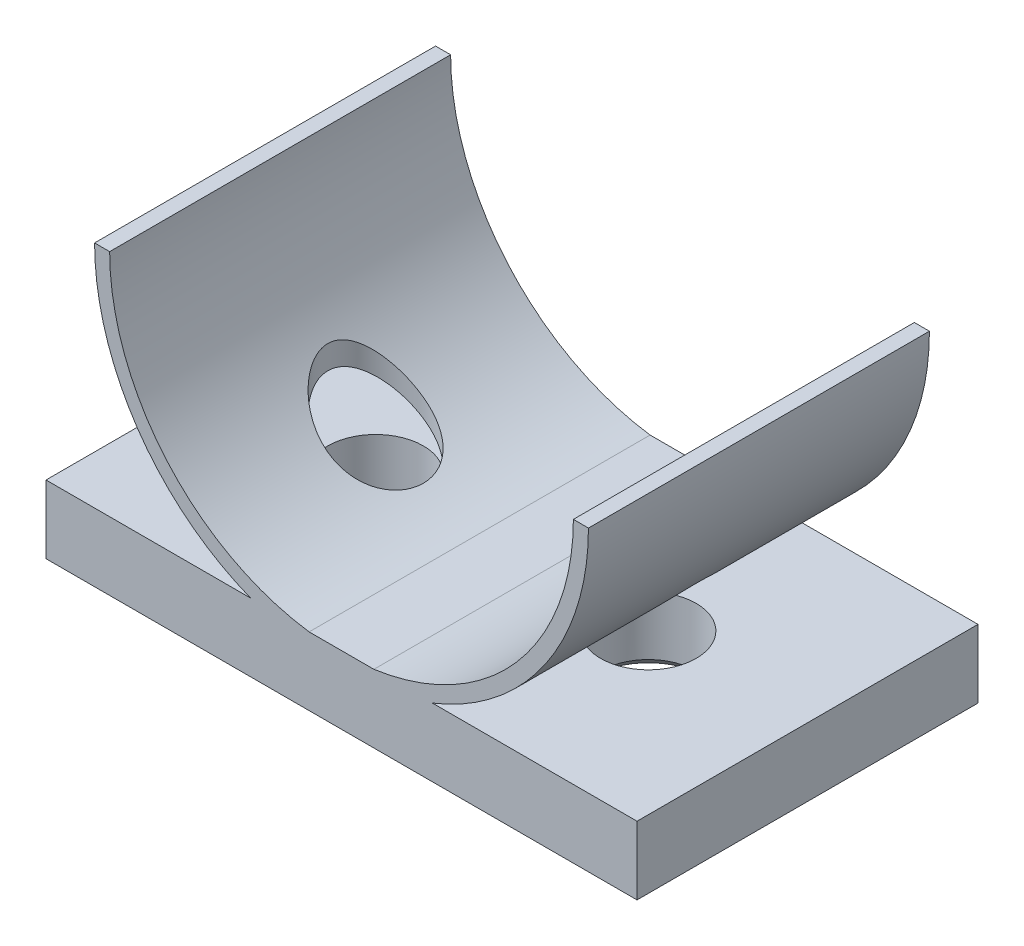
SolidWorks part; units mm, degrees
ref_plane "前视基准面" through (0, 0, 0) normal (0, 0, 1) x (1, 0, 0)
ref_plane "上视基准面" through (0, 0, 0) normal (0, 1, 0) x (1, 0, 0)
ref_plane "右视基准面" through (0, 0, 0) normal (1, 0, 0) x (0, 0, -1)
other "Configuration Table"
sketch "草图1" plane through (0, 0, 0) normal (0, 1, 0) x (1, 0, 0)
  line L1 (0, 0) -> (26, 0)
  line L2 (0, 0) -> (0, 15)
  line L3 (0, 15) -> (26, 15)
  line L4 (26, 0) -> (26, 15)
  dimension "D1" = 15
  dimension "D2" = 26
extrude "凸台-拉伸1" add sketch "草图1" along normal blind 3
sketch "草图3" plane through (0, 0, 0) normal (0, 0, 1) x (1, 0, 0)
  line L0 (13, 3) -> (13, 13.1) construction
  line L1 (0, 3) -> (26, 3) construction
  line L2 (13, 13.1) -> (-0.3081, 13.1) construction
  line L3 (0, 3) -> (9.0011, 3) construction
  line L4 (9.0011, 3) -> (11.5752, 3)
  line L7 (2.1371, 13.1) -> (2.8, 13.1)
  line L8 (23.2, 13.1) -> (23.8629, 13.1)
  line L10 (16.9989, 3) -> (22.3723, 3) construction
  line L11 (14.4248, 3) -> (16.9989, 3)
  arc A0 (2.8, 13.1) -> (11.5752, 3) centre (13, 13.1) ccw
  arc A1 (2.1371, 13.1) -> (9.0011, 3) centre (13, 13.1) ccw
  arc A2 (16.9989, 3) -> (23.8629, 13.1) centre (13, 13.1) ccw
  arc A3 (14.4248, 3) -> (23.2, 13.1) centre (13, 13.1) ccw
extrude "凸台-拉伸2" add sketch "草图3" against normal blind 15
sketch "草图4" plane through (0, 0, 0) normal (0, -1, 0) x (1, 0, 0)
  line L0 (0, -7.5) -> (7, -7.5) construction
  line L1 (0, -15) -> (0, 0) construction
  line L2 (13, 0) -> (13, -15) construction
  line L3 (0, 0) -> (26, 0) construction
  line L4 (26, -15) -> (0, -15) construction
  circle A0 centre (7, -7.5) radius 2.5
  circle A1 centre (19, -7.5) radius 2.5
  point P1 (7, -7.5)
  point P11 (19, -7.5)
  point P18 (7, -7.5)
  dimension "D1" = 7
hole_wizard "M5 螺纹孔2" positions "草图4" profile "草图6" tap size "M5" standard "GB"
sketch "草图6" plane through (7, 0, -7.5) normal (1, 0, 0) x (0, 0, -1)
  line L0 (0, 0) -> (0, 13.6618)
  line L1 (0, 13.6618) -> (2.1, 12.4)
  line L2 (2.1, 12.4) -> (2.1, 0.425)
  line L3 (2.1, 0.425) -> (2.525, 0)
  line L5 (2.525, 0) -> (0, 0)
  line L6 (-2.1, 0.425) -> (-2.525, 0) construction
  line L10 (0, 13.6618) -> (-2.1, 12.4) construction
  line L11 (0, -6.35) -> (0, 107.95) construction
  dimension "螺纹孔钻头直径" = 4.2
  dimension "螺纹孔钻头深度" = 12.4
  dimension "近端锥形沉头孔直径" = 5.05
  dimension "近端锥形沉头孔角度" = 90
  dimension "导头角度" = 118
cosmetic thread "孔螺蚊线2" parameters "D1"=10, "D2"=5
cosmetic thread "孔螺蚊线3" parameters "D1"=10, "D2"=5
